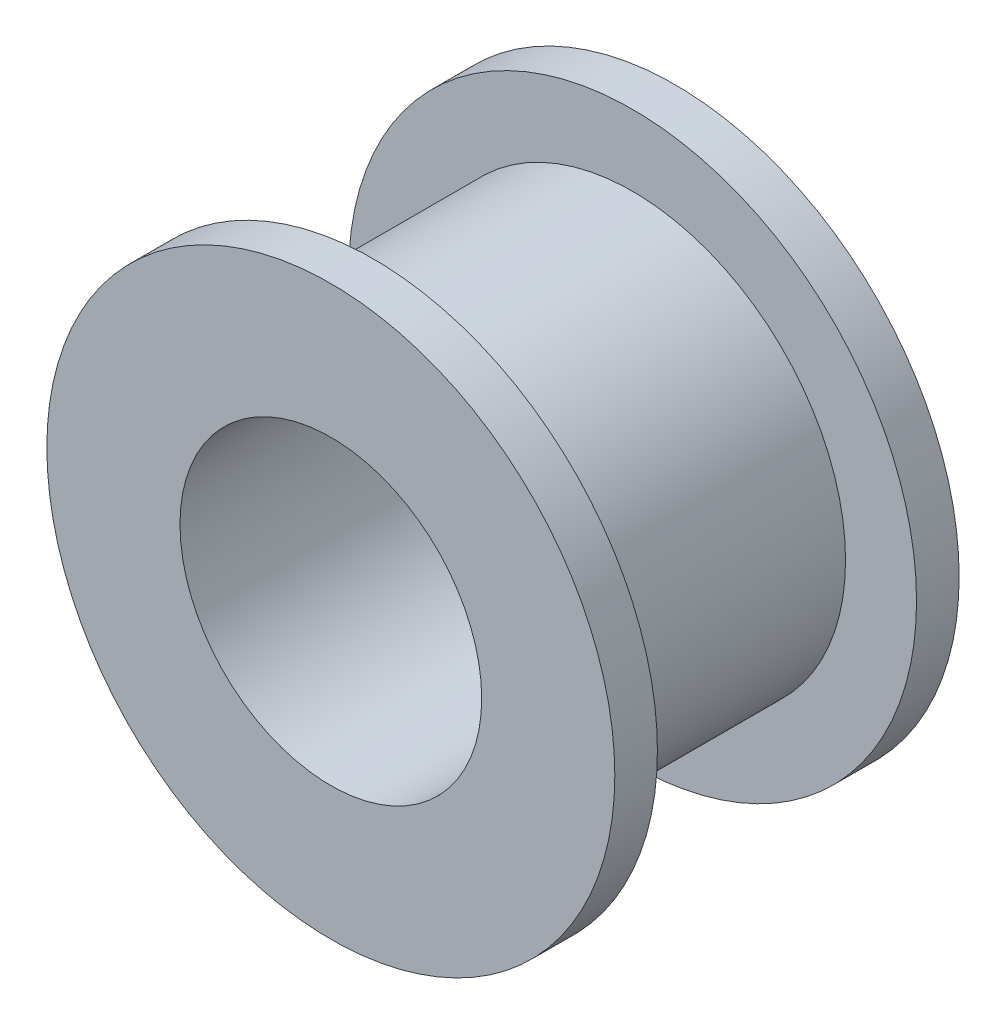
SolidWorks part; units mm, degrees
ref_plane "Front Plane" through (0, 0, 0) normal (0, 0, 1) x (1, 0, 0)
ref_plane "Top Plane" through (0, 0, 0) normal (0, 1, 0) x (1, 0, 0)
ref_plane "Right Plane" through (0, 0, 0) normal (1, 0, 0) x (0, 0, -1)
sketch "Sketch2" plane through (0, 0, 0) normal (0, 0, 1) x (1, 0, 0)
  circle A0 centre (0, 0) radius 8
  circle A1 centre (0, 0) radius 4.25
  dimension "D1" = 16
  dimension "D2" = 8.5
extrude "Boss-Extrude1" add sketch "Sketch2" along normal blind 16
ref_plane "Plane1" through (0, 0, 1.2) normal (0, 0, 1) x (1, 0, 0)
sketch "Sketch3" plane through (0, 0, 1.2) normal (0, 0, 1) x (1, 0, 0)
  circle A0 centre (0, 0) radius 6
  dimension "D1" = 12
ref_plane "Plane2" through (0, 0, 8.5) normal (0, 0, 1) x (1, 0, 0)
extrude "Cut-Extrude1" cut sketch "Sketch3" along normal up to surface (7.3 mm away) flip side to cut up to plane "Plane2"
sketch "Sketch4" plane through (0, 0, 16) normal (0, 0, 1) x (1, 0, 0)
  line L0 (0, 0) -> (0, 8) construction
  line L1 (0, 0) -> (8, 0) construction
  line L2 (0, 0) -> (0, -8) construction
  line L3 (0, 0) -> (-8, 0) construction
  circle A0 centre (0, 0) radius 8 construction
ref_plane "Plane3" through (0, 8, 0) normal (0, 1, 0) x (1, 0, 0)
ref_plane "Plane4" through (0, -8, 0) normal (0, 1, 0) x (1, 0, 0)
ref_plane "Plane5" through (8, 0, 0) normal (1, 0, 0) x (0, 0, -1)
sketch "Sketch5" plane through (0, 8, 0) normal (0, 1, 0) x (1, 0, 0)
  line L0 (0, -16) -> (0, -8.5) construction
  line L1 (0, -16) -> (-8, -16) construction
  line L2 (-8.8, -8.5) -> (8.8, -8.5) construction
  line L3 (-8, -12.25) -> (8, -12.25) construction
  line L5 (8, -55) -> (8, 55) construction
  circle A0 centre (0, -12.25) radius 1.75
  point P12 (0, -12.25)
  dimension "D1" = 3.5
sketch "Sketch6" plane through (8, 0, 0) normal (1, 0, 0) x (0, 0, -1)
  line L0 (-16, 0) -> (-8.5, 0) construction
  line L1 (-16, 0) -> (-16, -8) construction
  line L2 (-16, 0) -> (-16, 8) construction
  line L3 (-8.5, 8.8) -> (-8.5, -8.8) construction
  line L4 (-12.25, -8) -> (-12.25, 8) construction
  circle A0 centre (-12.25, 0) radius 1.75
  point P13 (-12.25, 0)
  dimension "D1" = 3.5
extrude "Cut-Extrude2" cut sketch "Sketch6" against normal up to next
extrude "Cut-Extrude3" cut sketch "Sketch5" against normal up to next
sketch "Sketch7" plane through (0, 0, 16) normal (0, 0, 1) x (1, 0, 0)
  circle A1 centre (0, 0) radius 8
  circle A2 centre (0, 0) radius 8
  dimension "D1" = 0
extrude "Cut-Extrude4" cut sketch "Sketch7" against normal blind 5.75 contours A2
sketch "Sketch8" plane through (8, 0, 0) normal (1, 0, 0) x (0, 0, -1)
  line L0 (-8.5, 0.9933) -> (-9.7, 0.9933)
  line L1 (-8.5, 8.8) -> (-8.5, -8.8) construction
  line L2 (-1.2, 2.7165) -> (0, 2.7165)
  line L3 (-1.2, 8.8) -> (-1.2, -8.8) construction
  line L4 (0, -8) -> (0, 8) construction
sketch "Sketch9" plane through (0, 0, 10.25) normal (0, 0, 1) x (1, 0, 0)
  circle A1 centre (0, 0) radius 8
  circle A2 centre (0, 0) radius 8
  dimension "D1" = 0
extrude "Cut-Extrude5" cut sketch "Sketch9" against normal up to vertex (0.55 mm away) up to point (8, 0.9933, 9.7)
sketch "Sketch10" plane through (0, 0, 0) normal (0, 0, -1) x (-1, 0, 0)
  line L0 (0, 8) -> (0, 4.25)
  line L1 (0, 0) -> (0, 8) construction
  circle A0 centre (0, 0) radius 4.25 construction
  circle A1 centre (0, 6.125) radius 1
  circle A2 centre (5.8252, 1.8927) radius 1
  circle A3 centre (3.6002, -4.9552) radius 1
  circle A4 centre (-3.6002, -4.9552) radius 1
  circle A5 centre (-5.8252, 1.8927) radius 1
  point P19 (0, 0)
  dimension "D1" = 5
extrude "Cut-Extrude6" cut sketch "Sketch10" against normal blind 1 contours A4 | A5 | A1 | A2 | A3
